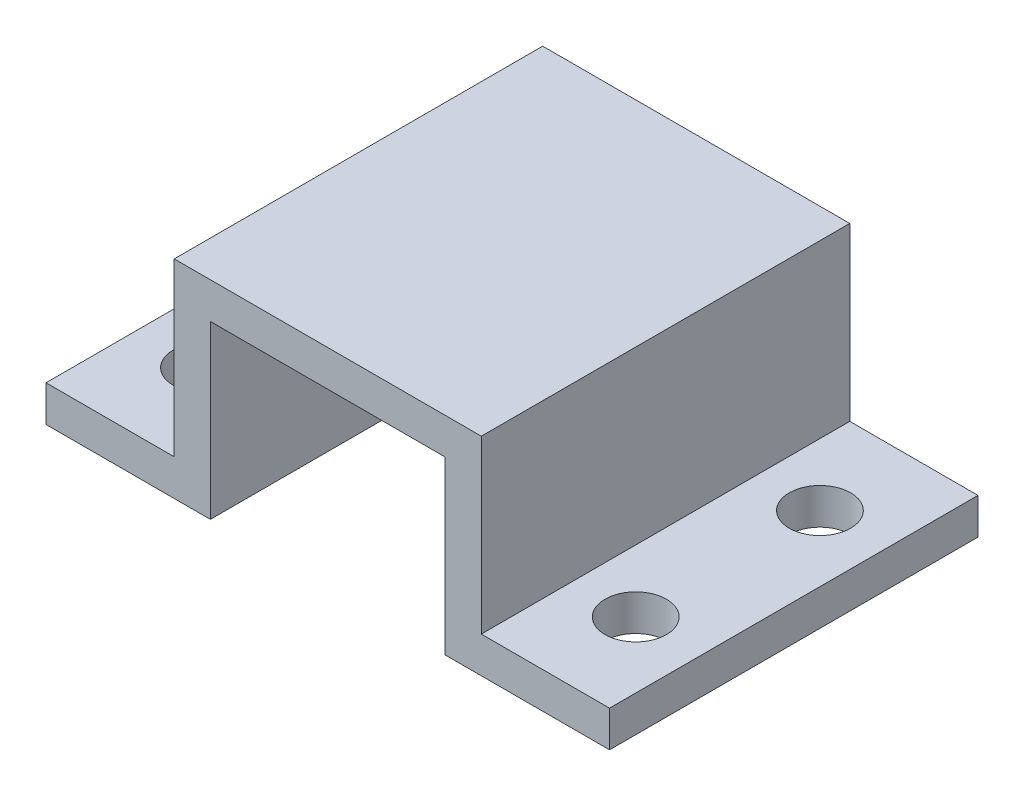
SolidWorks part; units mm, degrees
ref_plane "Front Plane" through (0, 0, 0) normal (0, 0, 1) x (1, 0, 0)
ref_plane "Top Plane" through (0, 0, 0) normal (0, 1, 0) x (1, 0, 0)
ref_plane "Right Plane" through (0, 0, 0) normal (1, 0, 0) x (0, 0, -1)
sketch "Sketch1" plane through (0, 0, 0) normal (0, 1, 0) x (1, 0, 0)
  line L0 (-6.3, 0) -> (-11.95, 0) construction
  line L1 (-8.3, 10.2) -> (-8.3, -10.2) construction
  line L2 (-15.6, -10.2) -> (-6.3, -10.2)
  line L3 (-15.6, -10.2) -> (-15.6, 10.2)
  line L4 (-15.6, 10.2) -> (-6.3, 10.2)
  line L5 (-6.3, -10.2) -> (-6.3, 10.2)
  line L8 (-6.3, 10.2) -> (6.3, 10.2)
  line L9 (0, 10.2) -> (0, -10.2) construction
  line L10 (-6.3, -10.2) -> (6.3, -10.2)
  line L14 (6.3, -10.2) -> (6.3, 10.2)
  line L15 (15.6, 10.2) -> (6.3, 10.2)
  line L16 (15.6, -10.2) -> (15.6, 10.2)
  line L17 (15.6, -10.2) -> (6.3, -10.2)
  line L18 (-6.5, 10.2) -> (-6.5, -10.2)
  line L19 (6.5, 10.2) -> (6.5, -10.2)
  line L20 (-11.95, 0) -> (-11.95, 10.2) construction
  circle A4 centre (-11.95, 5.1) radius 1.7
  circle A5 centre (-11.95, -5.1) radius 1.7
  circle A6 centre (11.95, -5.1) radius 1.7
  circle A7 centre (11.95, 5.1) radius 1.7
  point P20 (0, 0)
  dimension "D4" = 3.65
  dimension "D7" = 3.4
  dimension "D1" = 2
  dimension "D2" = 6.3
  dimension "D3" = 7.3
  dimension "D5" = 0.2
  dimension "D6" = 0.2
  dimension "D8" = 20.4
extrude "Boss-Extrude1" add sketch "Sketch1" along normal blind 2
sketch "Sketch2" plane through (0, 0, 0) normal (0, 1, 0) x (1, 0, 0)
  line L0 (-15.6, -10.2) -> (-6.5, -10.2) construction
  line L1 (-6.5, 10.2) -> (-8.5, 10.2)
  line L2 (-6.5, 10.2) -> (-6.5, -10.2)
  line L3 (-6.5, -10.2) -> (-8.5, -10.2)
  line L4 (-8.5, 10.2) -> (-8.5, -10.2)
  line L5 (0, 0) -> (0, 10.2) construction
  line L6 (6.5, 10.2) -> (-6.5, 10.2) construction
  line L7 (0, 0) -> (0, -10.2) construction
  line L8 (6.5, -10.2) -> (-6.5, -10.2) construction
  line L9 (8.5, 10.2) -> (8.5, -10.2)
  line L10 (6.5, -10.2) -> (8.5, -10.2)
  line L11 (6.5, 10.2) -> (6.5, -10.2)
  line L12 (6.5, 10.2) -> (8.5, 10.2)
  dimension "D1" = 2
extrude "Boss-Extrude2" add sketch "Sketch2" along normal blind 9.49
sketch "Sketch3" plane through (0, 9.49, 0) normal (0, 1, 0) x (1, 0, 0)
  line L1 (-8.5, 10.2) -> (8.5, 10.2)
  line L2 (-8.5, 10.2) -> (-8.5, -10.2)
  line L3 (-8.5, -10.2) -> (8.5, -10.2)
  line L4 (8.5, 10.2) -> (8.5, -10.2)
extrude "Boss-Extrude3" add sketch "Sketch3" along normal blind 2
sketch "Sketch4" plane through (0, 0, 10.2) normal (0, 0, 1) x (-1, 0, 0)
  line L0 (0, 0.51) -> (0, -9.49) construction
  line L1 (5.6, -5.49) -> (5.9149, -5.49)
  line L2 (5.6, -3.49) -> (5.6, -5.49)
  line L3 (5.9149, -3.49) -> (5.6, -3.49)
  line L4 (6.5, -9.49) -> (-6.5, -9.49) construction
  line L5 (-5.9149, -5.49) -> (-6.5, -5.49)
  line L6 (-6.5, -9.49) -> (-6.5, 0) construction
  line L7 (5.9149, -5.49) -> (6.5, -5.49)
  line L8 (6.5, -9.49) -> (6.5, 0) construction
  line L9 (15.6, 0) -> (6.5, 0) construction
  line L19 (3.25, 0.51) -> (-3.25, 0.51)
  line L20 (-5.9149, -3.49) -> (-5.6, -3.49)
  line L21 (-5.6, -3.49) -> (-5.6, -5.49)
  line L22 (-5.6, -5.49) -> (-5.9149, -5.49)
  line L23 (-3.25, -9.49) -> (3.25, -9.49)
  arc A0 (5.9149, -5.49) -> (3.25, -9.49) centre (0.0795, -4.49) cw
  arc A1 (3.25, 0.51) -> (5.9149, -3.49) centre (0.0795, -4.49) cw
  arc A9 (-3.25, 0.51) -> (-5.9149, -3.49) centre (-0.0795, -4.49) ccw
  arc A10 (-5.9149, -5.49) -> (-3.25, -9.49) centre (-0.0795, -4.49) ccw
  point P0 (3.25, -9.49)
  line M25 (6.5, 0) -> (6.5, -9.49)
  line M26 (6.5, -9.49) -> (-6.5, -9.49)
  line M27 (-6.5, -9.49) -> (-6.5, 0)
  dimension "D3" = 5.9205
  dimension "D1" = 3.25
  dimension "D2" = 4
  dimension "D4" = 2
  dimension "D5" = 0.3149
  dimension "D6" = 4
  dimension "D7" = 2.6649
  dimension "D8" = 0.51
extrude "Boss-Extrude4" [suppressed] add sketch "Sketch4" against normal offset from surface (16.4 mm away) 4 contours A10 L5 M27 M26 | L7 A0 M26 M25
